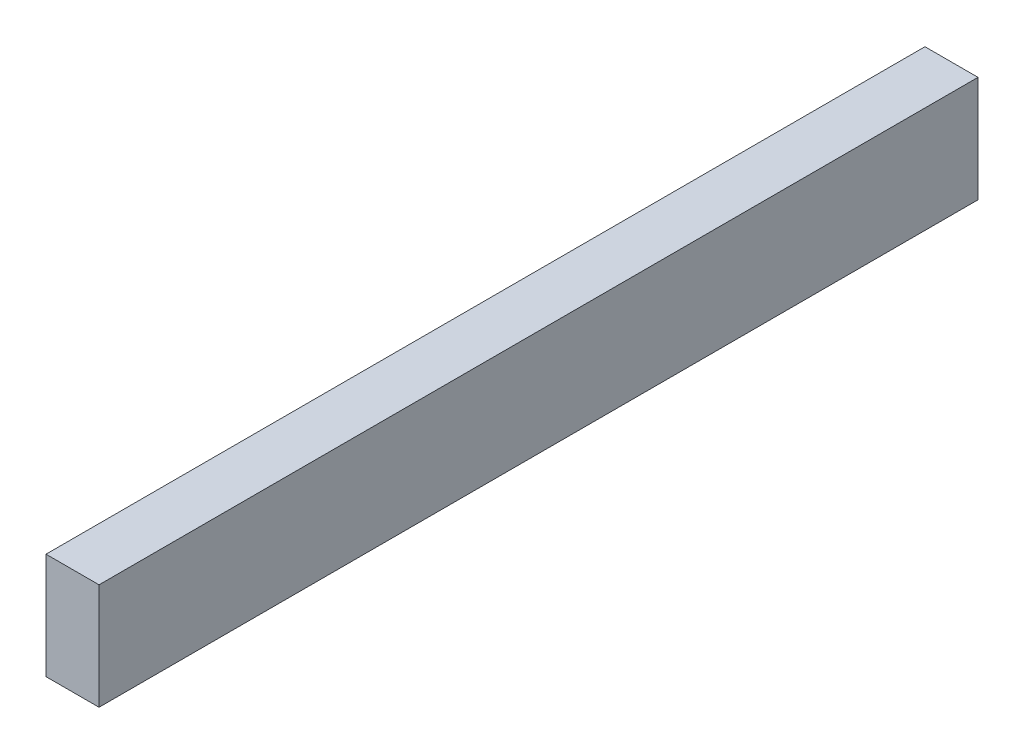
SolidWorks part; units mm, degrees
ref_plane "Front Plane" through (0, 0, 0) normal (0, 0, 1) x (1, 0, 0)
ref_plane "Top Plane" through (0, 0, 0) normal (0, 1, 0) x (1, 0, 0)
ref_plane "Right Plane" through (0, 0, 0) normal (1, 0, 0) x (0, 0, -1)
sketch "Sketch1" plane through (0, 0, 0) normal (0, 0, 1) x (1, 0, 0)
  line L1 (0, 0) -> (22.225, 0)
  line L2 (0, 0) -> (0, 44.45)
  line L3 (0, 44.45) -> (22.225, 44.45)
  line L4 (22.225, 0) -> (22.225, 44.45)
  dimension "D1" = 22.225
  dimension "D2" = 44.45
extrude "Boss-Extrude1" add sketch "Sketch1" along normal blind 368.3
